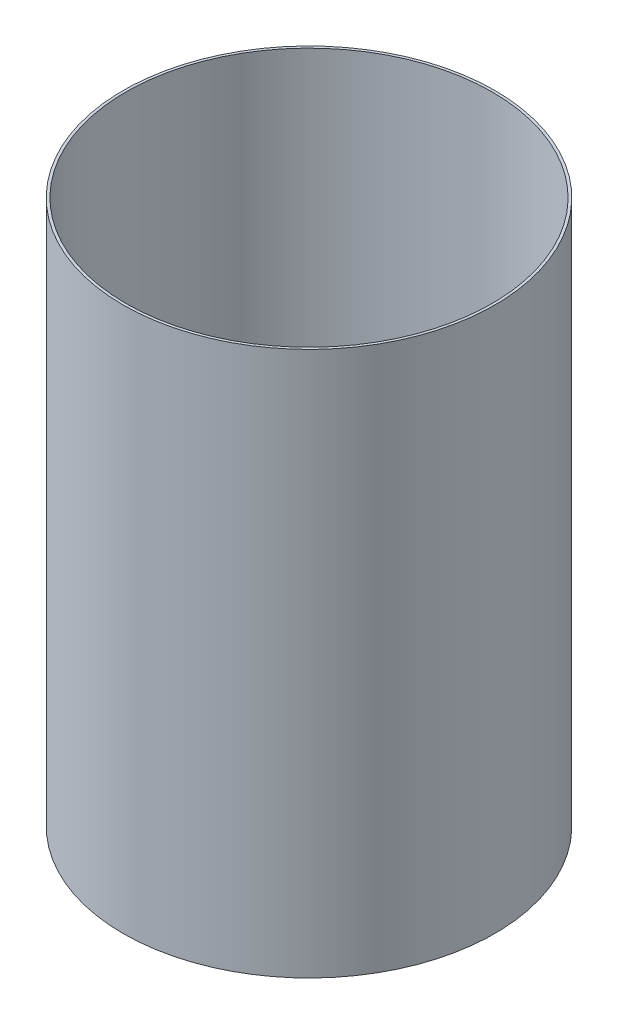
SolidWorks part; units mm, degrees
material "6061 Alloy"
ref_plane "Front Plane" through (0, 0, 0) normal (0, 0, 1) x (1, 0, 0)
ref_plane "Top Plane" through (0, 0, 0) normal (0, 1, 0) x (1, 0, 0)
ref_plane "Right Plane" through (0, 0, 0) normal (1, 0, 0) x (0, 0, -1)
sketch "Sketch1" plane through (0, 0, 0) normal (0, 1, 0) x (1, 0, 0)
  circle A0 centre (0, 0) radius 71
  circle A1 centre (0, 0) radius 70
  dimension "D1" = 142
  dimension "D2" = 140
extrude "Boss-Extrude1" add sketch "Sketch1" along normal blind 206
sketch "Sketch2" plane through (0, 0, 0) normal (0, -1, 0) x (1, 0, 0)
  circle A0 centre (0, 0) radius 71
extrude "Boss-Extrude2" add sketch "Sketch2" along normal blind 2
